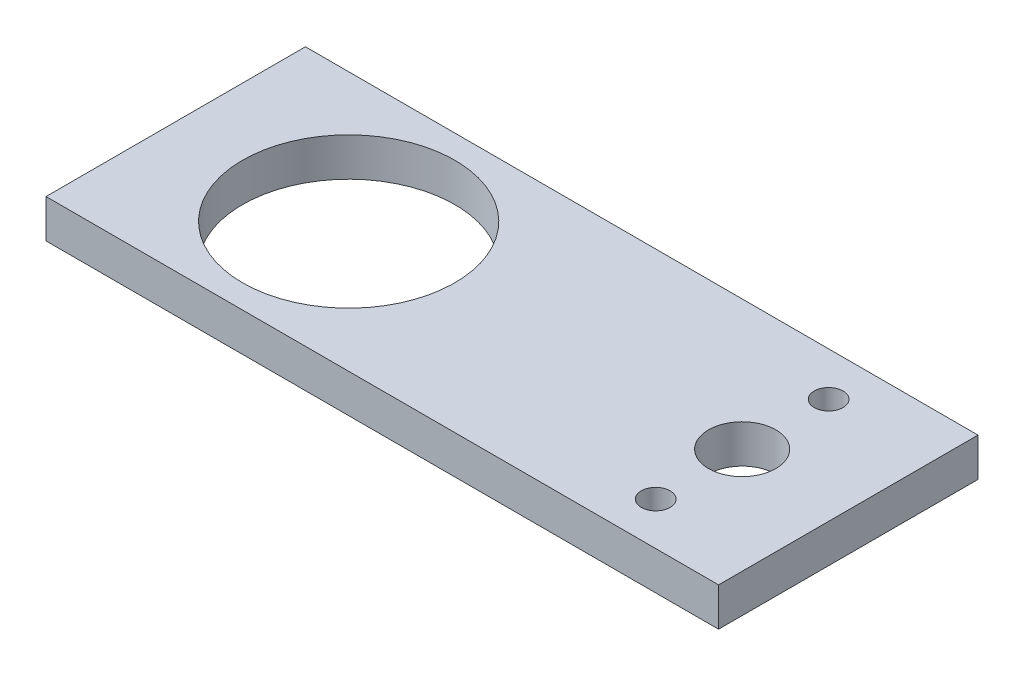
SolidWorks part; units mm, degrees
ref_plane "Front Plane" through (0, 0, 0) normal (0, 0, 1) x (1, 0, 0)
ref_plane "Top Plane" through (0, 0, 0) normal (0, 1, 0) x (1, 0, 0)
ref_plane "Right Plane" through (0, 0, 0) normal (1, 0, 0) x (0, 0, -1)
sketch "Sketch1" plane through (0, 0, 0) normal (0, 1, 0) x (1, 0, 0)
  line L1 (-41.595, 10.8942) -> (28.405, 10.8942)
  line L2 (-41.595, 10.8942) -> (-41.595, -16.1058)
  line L3 (-41.595, -16.1058) -> (28.405, -16.1058)
  line L4 (28.405, 10.8942) -> (28.405, -16.1058)
  circle A2 centre (17.405, -2.6507) radius 3.5
  circle A3 centre (17.405, 6.3493) radius 1.5
  circle A4 centre (17.405, -11.6507) radius 1.5
  circle A5 centre (-23.595, -2.6058) radius 11.05
  dimension "D8" = 7
  dimension "D9" = 3
  dimension "D10" = 3
  dimension "D13" = 22.1
  dimension "D1" = 27
  dimension "D2" = 70
  dimension "D11" = 9
  dimension "D12" = 9
  dimension "D14" = 13.5
  dimension "D15" = 11
  dimension "D16" = 52
extrude "Boss-Extrude1" add sketch "Sketch1" along normal blind 4
